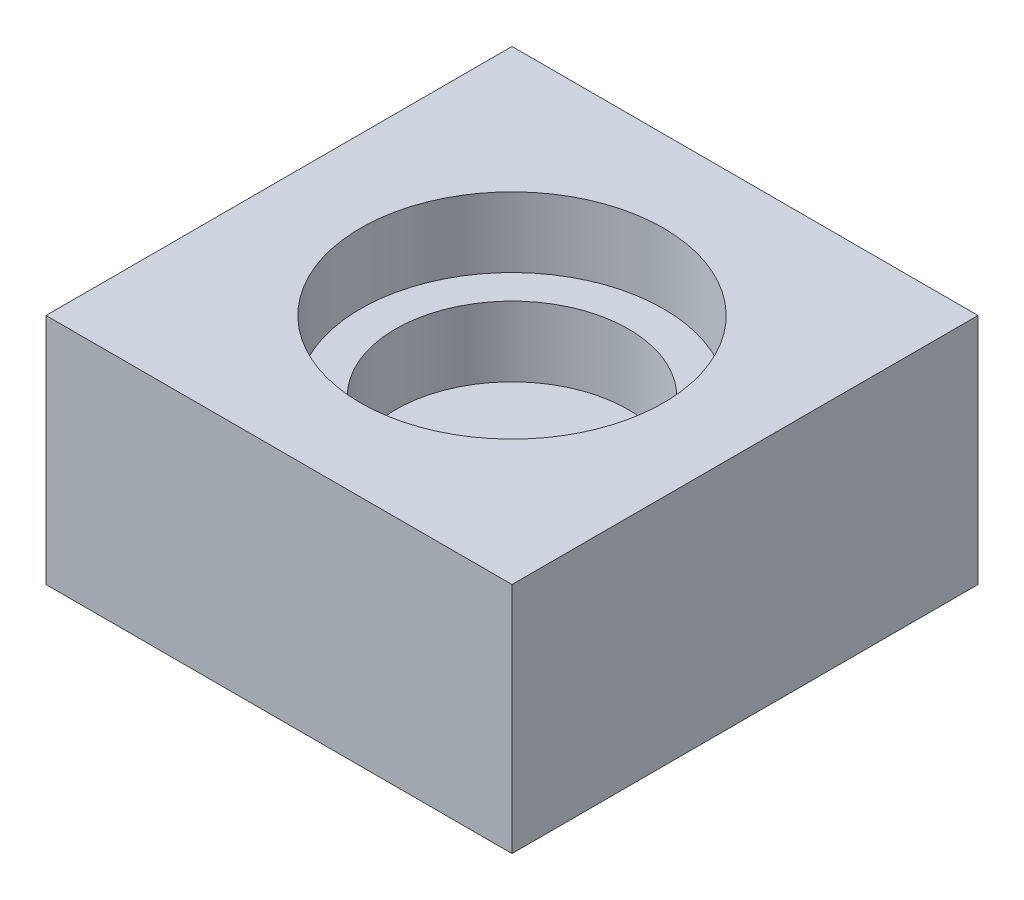
SolidWorks part; units mm, degrees
ref_plane "Спереди" through (0, 0, 0) normal (0, 0, 1) x (1, 0, 0)
ref_plane "Сверху" through (0, 0, 0) normal (0, 1, 0) x (1, 0, 0)
ref_plane "Справа" through (0, 0, 0) normal (1, 0, 0) x (0, 0, -1)
sketch "Эскиз1" plane through (0, 0, 0) normal (0, 1, 0) x (1, 0, 0)
  line L1 (0, 0) -> (40, 0)
  line L2 (0, 0) -> (0, 40)
  line L3 (0, 40) -> (40, 40)
  line L4 (40, 0) -> (40, 40)
extrude "Бобышка-Вытянуть1" add sketch "Эскиз1" along normal blind 20
sketch "Эскиз2" plane through (0, 20, 0) normal (0, 1, 0) x (1, 0, 0)
  line L0 (40, 0) -> (40, 40) construction
  line L1 (40, 40) -> (0, 40) construction
  circle A0 centre (20, 20) radius 13
  dimension "D1" = 20
  dimension "D3" = 26
  dimension "D2" = 20
extrude "Вырез-Вытянуть1" cut sketch "Эскиз2" against normal blind 6
sketch "Эскиз3" plane through (0, 14, 0) normal (0, 1, 0) x (1, 0, 0)
  circle A0 centre (20, 20) radius 10
extrude "Вырез-Вытянуть2" cut sketch "Эскиз3" against normal blind 6
